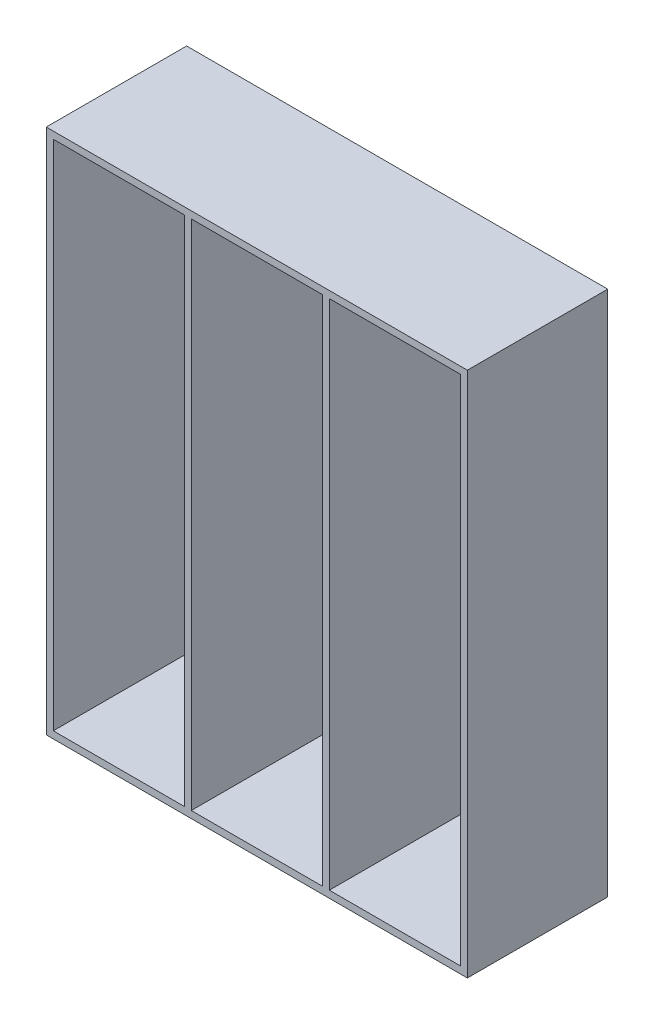
SolidWorks part; units mm, degrees
ref_plane "Front Plane" through (0, 0, 0) normal (0, 0, 1) x (1, 0, 0)
ref_plane "Top Plane" through (0, 0, 0) normal (0, 1, 0) x (1, 0, 0)
ref_plane "Right Plane" through (0, 0, 0) normal (1, 0, 0) x (0, 0, -1)
sketch "Sketch1" plane through (0, 0, 0) normal (0, 0, 1) x (1, 0, 0)
  line L1 (-30, -37.5) -> (30, -37.5)
  line L2 (-30, -37.5) -> (-30, 37.5)
  line L3 (-30, 37.5) -> (30, 37.5)
  line L4 (30, -37.5) -> (30, 37.5)
  line L5 (-30, -37.5) -> (30, 37.5) construction
  line L6 (-30, 37.5) -> (30, -37.5) construction
  dimension "D1" = 30
  dimension "D2" = 30
  dimension "D3" = 37.5
  dimension "D4" = 37.5
extrude "Boss-Extrude1" add sketch "Sketch1" against normal blind 20
sketch "Sketch2" plane through (0, 0, 0) normal (0, 0, 1) x (1, 0, 0)
  line L1 (-29, -36.5) -> (-10.3333, -36.5)
  line L2 (-29, -36.5) -> (-29, 36.5)
  line L3 (-29, 36.5) -> (-10.3333, 36.5)
  line L4 (-10.3333, -36.5) -> (-10.3333, 36.5)
  line L5 (-29, -36.5) -> (-10.3333, 36.5) construction
  line L6 (-29, 36.5) -> (-10.3333, -36.5) construction
  dimension "D1" = 10.3333
  dimension "D2" = 29
  dimension "D3" = 36.5
  dimension "D4" = 36.5
extrude "Cut-Extrude1" cut sketch "Sketch2" against normal blind 19
sketch "Sketch3" plane through (0, 0, 0) normal (0, 0, 1) x (1, 0, 0)
  line L1 (-9.3333, -36.5) -> (9.3333, -36.5)
  line L2 (-9.3333, -36.5) -> (-9.3333, 36.5)
  line L3 (-9.3333, 36.5) -> (9.3333, 36.5)
  line L4 (9.3333, -36.5) -> (9.3333, 36.5)
  line L5 (-9.3333, -36.5) -> (9.3333, 36.5) construction
  line L6 (-9.3333, 36.5) -> (9.3333, -36.5) construction
  dimension "D1" = 9.3333
  dimension "D2" = 9.3333
  dimension "D3" = 36.5
  dimension "D4" = 36.5
extrude "Cut-Extrude2" cut sketch "Sketch3" against normal blind 19
sketch "Sketch4" plane through (0, 0, 0) normal (0, 0, 1) x (1, 0, 0)
  line L1 (10.3333, -36.5) -> (29, -36.5)
  line L2 (10.3333, -36.5) -> (10.3333, 36.5)
  line L3 (10.3333, 36.5) -> (29, 36.5)
  line L4 (29, -36.5) -> (29, 36.5)
  line L5 (10.3333, -36.5) -> (29, 36.5) construction
  line L6 (10.3333, 36.5) -> (29, -36.5) construction
  dimension "D1" = 10.3333
  dimension "D2" = 29
  dimension "D3" = 36.5
  dimension "D4" = 36.5
extrude "Cut-Extrude3" cut sketch "Sketch4" against normal blind 19
